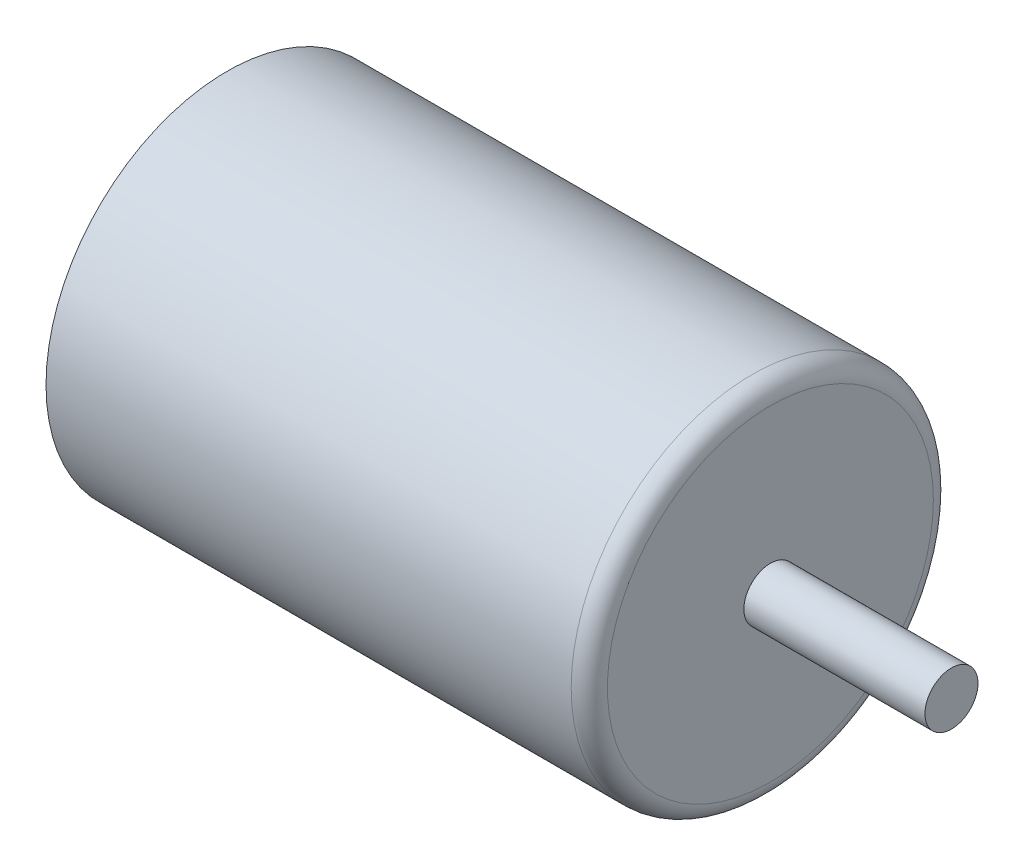
SolidWorks part; units mm, degrees
ref_plane "Front Plane" through (0, 0, 0) normal (0, 0, 1) x (1, 0, 0)
ref_plane "Top Plane" through (0, 0, 0) normal (0, 1, 0) x (1, 0, 0)
ref_plane "Right Plane" through (0, 0, 0) normal (1, 0, 0) x (0, 0, -1)
sketch "Sketch1" plane through (0, 0, 0) normal (1, 0, 0) x (0, 0, -1)
  circle A0 centre (0, 0) radius 25.4
extrude "Boss-Extrude1" add sketch "Sketch1" along normal blind 76.2
sketch "Sketch2" plane through (76.2, 0, 0) normal (1, 0, 0) x (0, 0, -1)
  circle A0 centre (0, 0) radius 3.7205
extrude "Boss-Extrude2" add sketch "Sketch2" along normal blind 25.4
fillet "Fillet1" radius 2.54 1 edges at (76.2, 0, -25.4)
